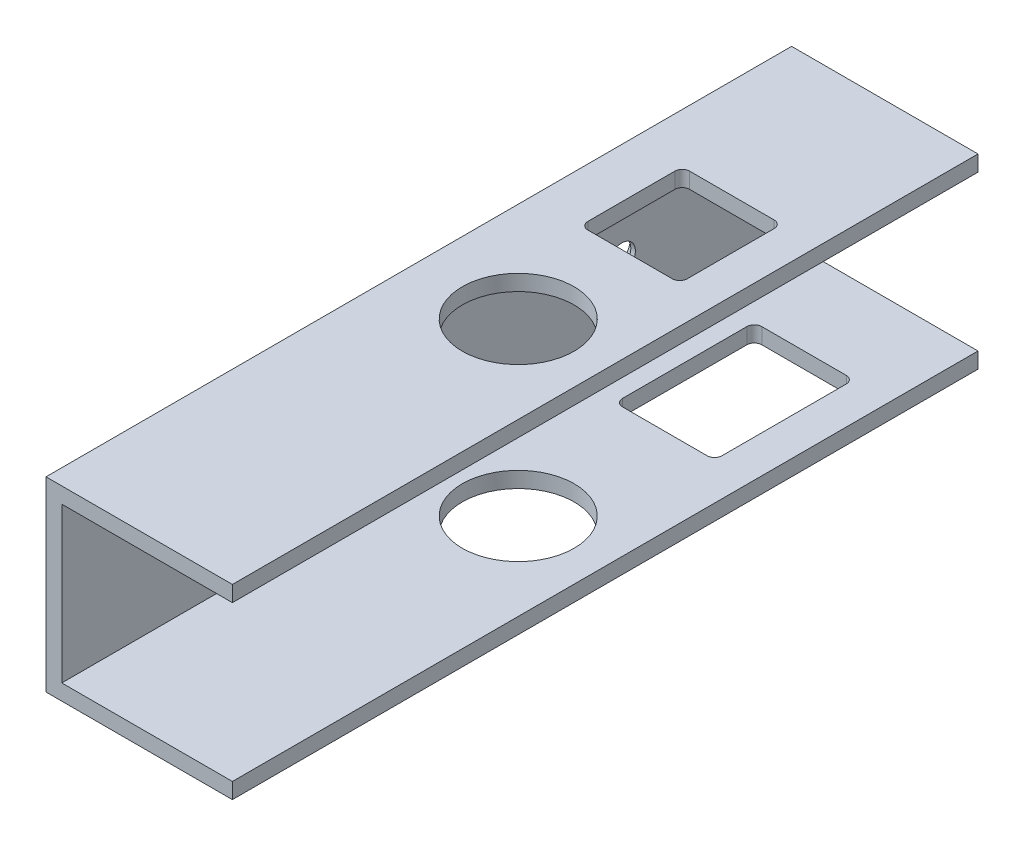
SolidWorks part; units mm, degrees
ref_plane "Front Plane" through (0, 0, 0) normal (0, 0, 1) x (1, 0, 0)
ref_plane "Top Plane" through (0, 0, 0) normal (0, 1, 0) x (1, 0, 0)
ref_plane "Right Plane" through (0, 0, 0) normal (1, 0, 0) x (0, 0, -1)
sketch "Sketch1" plane through (0, 0, 0) normal (0, 0, 1) x (1, 0, 0)
  line L0 (0, -37.5) -> (0, 37.5)
  line L1 (0, 37.5) -> (75, 37.5)
  line L2 (75, 37.5) -> (75, 31.15)
  line L3 (75, 31.15) -> (6.35, 31.15)
  line L4 (6.35, 31.15) -> (6.35, -31.15)
  line L5 (6.35, -31.15) -> (75, -31.15)
  line L6 (75, -31.15) -> (75, -37.5)
  line L7 (75, -37.5) -> (0, -37.5)
  line L8 (0, 0) -> (6.35, 0) construction
  dimension "D1" = 75
  dimension "D2" = 75
  dimension "D3" = 6.35
extrude "Boss-Extrude1" add sketch "Sketch1" along normal blind 300
sketch "Sketch2" plane through (0, 37.5, 0) normal (0, 1, 0) x (1, 0, 0)
  line L0 (0, -300) -> (0, 0) construction
  line L1 (75, -300) -> (0, -300) construction
  circle A0 centre (40, -150) radius 22.5
  dimension "D1" = 45
  dimension "D2" = 40
  dimension "D3" = 150
extrude "Cut-Extrude1" cut sketch "Sketch2" against normal through all
sketch "Sketch3" plane through (0, -37.5, 0) normal (0, -1, 0) x (1, 0, 0)
  line L0 (20, 91) -> (20, 35)
  line L1 (20, 91) -> (60, 91)
  line L2 (20, 35) -> (60, 35)
  line L3 (60, 91) -> (60, 35)
  line L4 (20, 91) -> (60, 35) construction
  line L5 (20, 35) -> (60, 91) construction
  line L6 (40, 91) -> (40, 150) construction
  circle A0 centre (40, 150) radius 22.5 construction
  point P1 (40, 63)
  dimension "D1" = 59
  dimension "D2" = 40
  dimension "D3" = 56
extrude "Cut-Extrude2" cut sketch "Sketch3" against normal blind 10
sketch "Sketch4" plane through (0, 37.5, 0) normal (0, 1, 0) x (1, 0, 0)
  line L0 (60, -105) -> (60, -64)
  line L1 (60, -105) -> (20, -105)
  line L2 (60, -64) -> (20, -64)
  line L3 (20, -105) -> (20, -64)
  line L4 (60, -105) -> (20, -64) construction
  line L5 (60, -64) -> (20, -105) construction
  line L6 (40, -105) -> (40, -150) construction
  circle A0 centre (40, -150) radius 22.5 construction
  point P1 (40, -84.5)
  dimension "D1" = 86
  dimension "D2" = 45
  dimension "D3" = 40
extrude "Cut-Extrude3" cut sketch "Sketch4" against normal blind 10
fillet "Fillet1" radius 3 8 edges at (60, -34.325, 35) (60, -34.325, 91) (20, -34.325, 91) (20, -34.325, 35) (60, 34.325, 105) (60, 34.325, 64) (20, 34.325, 64) (20, 34.325, 105)
hole_wizard "CSK for M10 Countersunk Flat Head Screw1" positions "Sketch6" profile "Sketch5" countersink size "M10" standard "ISO"
sketch "Sketch6" plane through (0, 0, 0) normal (-1, 0, 0) x (0, 0, 1)
  point P0 (74.7041, 4.0111)
sketch "Sketch5" plane through (0, 4.0111, 74.7041) normal (0, 1, 0) x (0, 0, 1)
  line L0 (0, 0) -> (0, 23.3077)
  line L1 (0, 23.3077) -> (5.5, 20.003)
  line L2 (5.5, 20.003) -> (5.5, 4.5)
  line L3 (5.5, 4.5) -> (10, 0)
  line L5 (10, 0) -> (0, 0)
  line L6 (-5.5, 4.5) -> (-10, 0) construction
  line L10 (0, 23.3077) -> (-5.5, 20.003) construction
  line L11 (0, -6.35) -> (0, 107.95) construction
  dimension "Hole Dia." = 11
  dimension "Hole Depth" = 20.003
  dimension "Near C'Sink Dia." = 20
  dimension "Near C'Sink Angle" = 90
  dimension "Drill Angle" = 118
